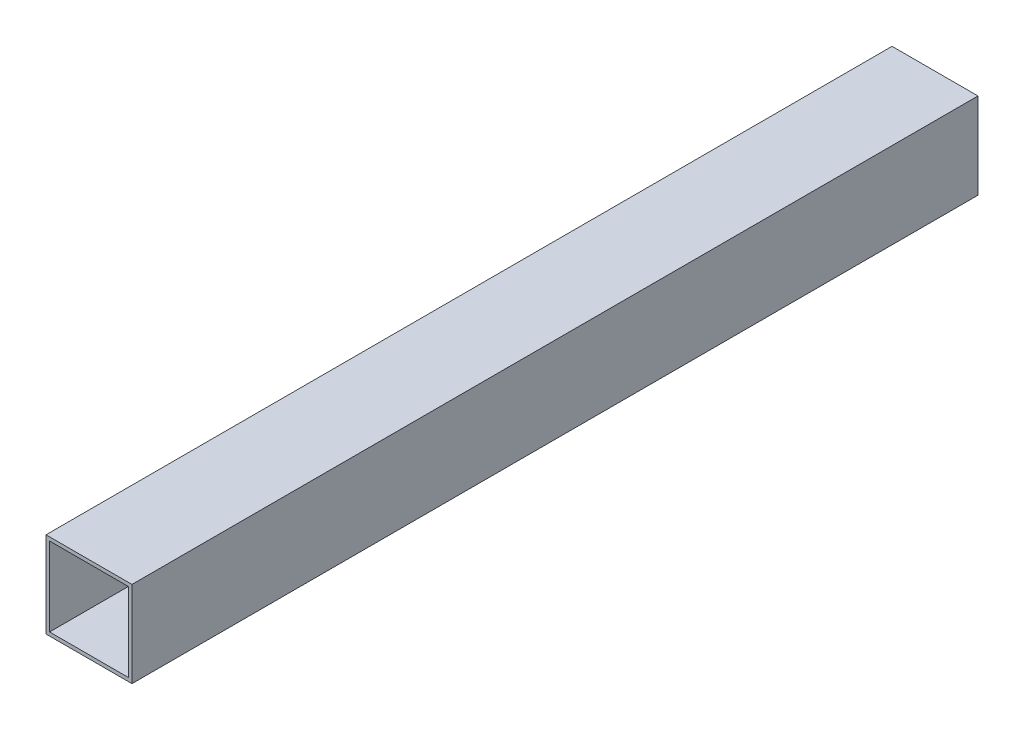
SolidWorks part; units mm, degrees
ref_plane "Front Plane" through (0, 0, 0) normal (0, 0, 1) x (1, 0, 0)
ref_plane "Top Plane" through (0, 0, 0) normal (0, 1, 0) x (1, 0, 0)
ref_plane "Right Plane" through (0, 0, 0) normal (1, 0, 0) x (0, 0, -1)
sketch "Sketch1" plane through (0, 0, 0) normal (0, 0, 1) x (1, 0, 0)
  line L0 (-34.925, 34.925) -> (34.925, 34.925)
  line L1 (-38.1, -38.1) -> (38.1, -38.1)
  line L2 (-38.1, -38.1) -> (-38.1, 38.1)
  line L3 (-38.1, 38.1) -> (38.1, 38.1)
  line L4 (38.1, -38.1) -> (38.1, 38.1)
  line L5 (-38.1, -38.1) -> (38.1, 38.1) construction
  line L6 (-38.1, 38.1) -> (38.1, -38.1) construction
  line L7 (34.925, -34.925) -> (34.925, 34.925)
  line L8 (-34.925, -34.925) -> (34.925, -34.925)
  line L9 (-34.925, -34.925) -> (-34.925, 34.925)
  point P0 (0, 0)
  dimension "D1" = 76.2
  dimension "D2" = 3.175
extrude "Boss-Extrude1" add sketch "Sketch1" along normal mid plane 750 contours L9 L8 L7 L0 | L3 L4 L1 L2
